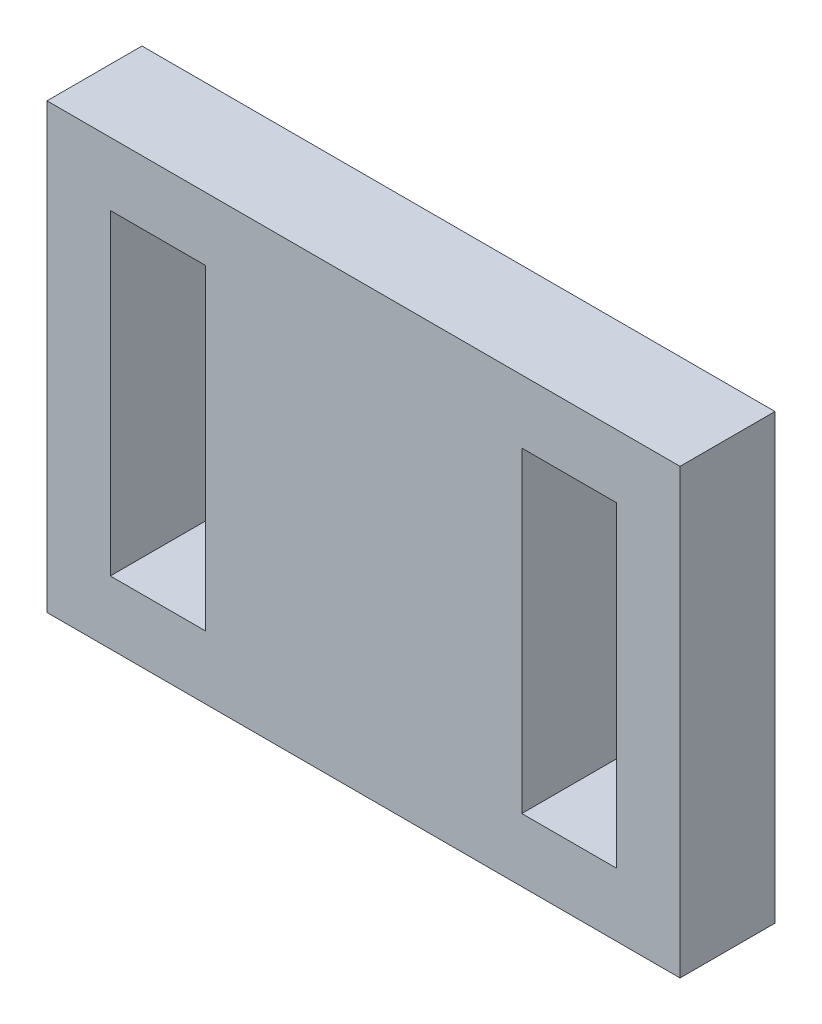
SolidWorks part; units mm, degrees
material "Thornel Mat VMA"
ref_plane "前视基准面" through (0, 0, 0) normal (0, 0, 1) x (1, 0, 0)
ref_plane "上视基准面" through (0, 0, 0) normal (0, 1, 0) x (1, 0, 0)
ref_plane "右视基准面" through (0, 0, 0) normal (1, 0, 0) x (0, 0, -1)
sketch "草图1" plane through (0, 0, 0) normal (0, 0, 1) x (1, 0, 0)
  line L0 (0, -55) -> (0, 55) construction
  line L1 (-10, 7) -> (10, 7)
  line L2 (-10, 7) -> (-10, -7)
  line L3 (-10, -7) -> (10, -7)
  line L4 (10, 7) -> (10, -7)
  line L5 (-10, 7) -> (10, -7) construction
  line L6 (-10, -7) -> (10, 7) construction
  line L7 (8, 5) -> (5, 5)
  line L8 (8, 5) -> (8, -5)
  line L9 (8, -5) -> (5, -5)
  line L10 (5, 5) -> (5, -5)
  line L11 (-8, -5) -> (-5, -5)
  line L12 (-5, 5) -> (-5, -5)
  line L13 (-8, 5) -> (-5, 5)
  line L14 (-8, 5) -> (-8, -5)
  point P0 (0, 0)
  dimension "D1" = 20
  dimension "D2" = 14
  dimension "D3" = 10
  dimension "D4" = 2
  dimension "D5" = 2
  dimension "D6" = 3
extrude "凸台-拉伸1" add sketch "草图1" along normal blind 3
